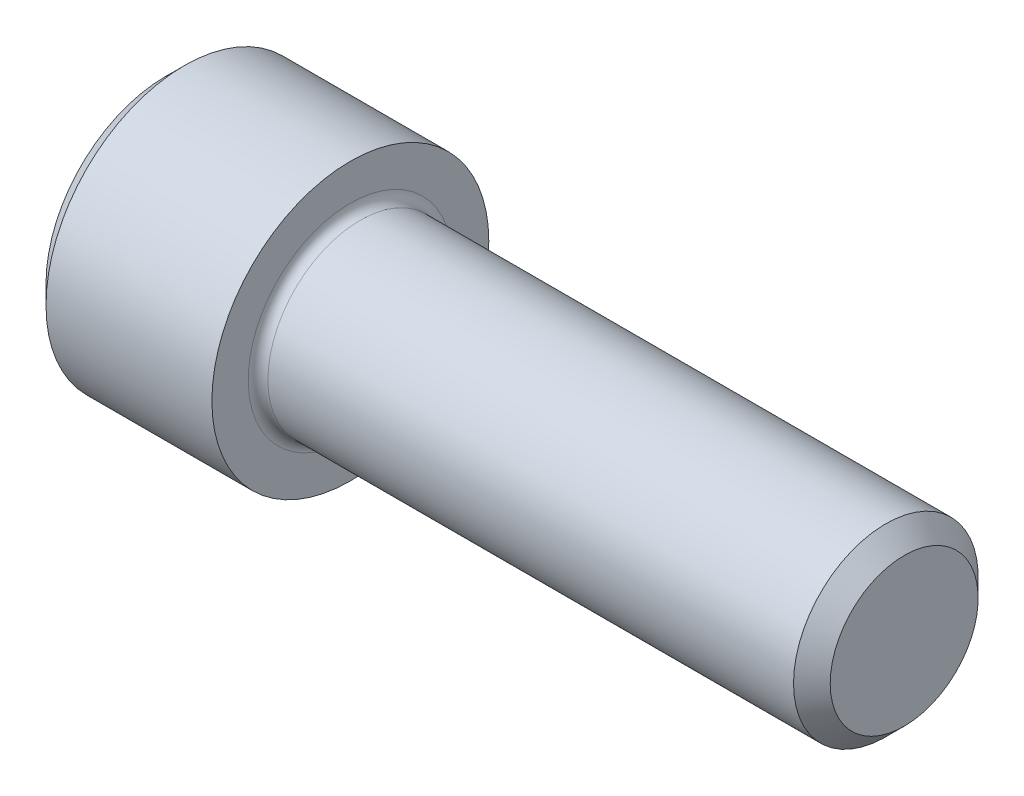
SolidWorks part; units mm, degrees
revolve "Base-Revolve" add sketch "BodySke"
sketch "BodySke" plane through (0, 0, 0) normal (0, 0, 1) x (1, 0, 0)
  line L0 (0, 0) -> (0, 6.1786)
  line L1 (0.9652, 7.1438) -> (9.525, 7.1438)
  line L2 (9.525, 7.1438) -> (9.525, 4.7625)
  line L3 (9.525, 4.7625) -> (37.1539, 4.7625)
  line L4 (38.1, 3.8163) -> (38.1, 0)
  line L5 (38.1, 0) -> (0, 0)
  line L6 (-31.75, 0) -> (127, 0) construction
  line L7 (0, 6.1786) -> (0.9652, 7.1438)
  line L8 (38.1, 3.8163) -> (37.1539, 4.7625)
  line L9 (0, -6.1786) -> (0.9652, -7.1437) construction
  line L10 (38.1, -3.8163) -> (37.1539, -4.7625) construction
  line L11 (11.1125, 9.525) -> (11.1125, 3.175) construction
  line L12 (9.525, 9.525) -> (9.525, 3.175) construction
  line L13 (0, 9.525) -> (0, 3.175) construction
  dimension "Diameter" = 9.525
  dimension "Head_ht" = 9.525
  dimension "Length" = 28.575
  dimension "Body_ch_ang" = 45
  dimension "Head_dia" = 14.2875
  dimension "Head_ch_ang" = 45
  dimension "Head_side_ht" = 8.5598
  dimension "Minor_dia" = 7.6327
  dimension "Advance" = 1.5875
  dimension "Thread_nom" = 28.575
  dimension "Thread_length" = 38.1
cosmetic thread "ThreadCosmetic" [suppressed]
fillet "Fillet1" radius 0.508 1 edges at (9.525, 0, 4.7625)
ref_plane "Plane1" through (0, 0, 0) normal (0, 0, 1) x (1, 0, 0)
ref_plane "Plane2" through (0, 0, 0) normal (0, 1, 0) x (1, 0, 0)
ref_plane "Plane3" through (0, 0, 0) normal (1, 0, 0) x (0, 0, -1)
sketch "Sketch2" plane through (0, 0, 0) normal (0, 0, 1) x (1, 0, 0)
  line L0 (0, 3.9688) -> (4.6228, 3.9688)
  line L1 (4.6228, 3.9688) -> (6.9142, 0)
  line L2 (-31.75, 0) -> (127, 0) construction
  line L3 (6.9142, 0) -> (0, 0)
  line L4 (0, 0) -> (0, 3.9688)
  line L5 (0, 6.1786) -> (0, -6.1786) construction
  line L6 (0, 0) -> (47.625, 0) construction
  line L7 (9.525, -7.1438) -> (9.525, 7.1438) construction
  dimension "D1" = 3.9688
  dimension "D2" = 60
revolve "Hex-PreBroach" cut sketch "Sketch2" angle 360 about L6
sketch "Sketch3" plane through (0, 0, 0) normal (-1, 0, 0) x (0, 0.5, 0.866)
  line L0 (2.2914, 3.9688) -> (-2.2914, 3.9688)
  line L1 (-2.2914, 3.9688) -> (-4.5827, 0)
  line L2 (2.2914, 3.9688) -> (4.5827, 0)
  line L3 (2.2914, -3.9688) -> (4.5827, 0)
  line L4 (2.2914, -3.9688) -> (-2.2914, -3.9688)
  line L5 (-2.2914, -3.9688) -> (-4.5827, 0)
  dimension "D1" = 3.9688
  dimension "D2" = 3.9688
  dimension "Hex_size" = 7.9375
extrude "Hex" cut sketch "Sketch3" against normal blind 4.6228
sketch "Sketch4" plane through (0, 0, 0) normal (-1, 0, 0) x (0, 0, 1)
  line L0 (0, 0) -> (4.826, 0)
  line L1 (0, 0) -> (6.1484, 3.5498) construction
  line L2 (0, 0) -> (2.413, 4.1794)
  line L3 (3.9437, 0.9277) -> (4.6393, 1.3293)
  line L4 (2.7753, 2.9514) -> (3.4709, 3.3531)
  arc A0 (3.9437, 0.9277) -> (2.7753, 2.9514) centre (0, 0) ccw
  arc A1 (4.826, 0) -> (4.6393, 1.3293) centre (0, 0) ccw
  arc A2 (2.413, 4.1794) -> (3.4709, 3.3531) centre (0, 0) cw
  dimension "D1" = 30
  dimension "D2" = 60
  dimension "Spline_p_dim" = 2.3368
  dimension "D3" = 1.1684
extrude "Spline" [suppressed] cut sketch "Sketch4" against normal blind 4.6228
pattern_circular "CirPattern1" [suppressed] count 6 every 60
sketch "Sketch5" plane through (0, 0, 0) normal (0, 0, 1) x (1, 0, 0)
  line L0 (-31.75, 0) -> (127, 0) construction
  line L2 (0, 6.1786) -> (0, -6.1786) construction
  circle A0 centre (3.1242, 0) radius 0.8065
  dimension "Drilled_hole_dia" = 1.6129
  dimension "Drilled_hole_loc" = 3.1242
extrude "Hole" [suppressed] cut sketch "Sketch5" against normal through all and the other way through all
pattern_circular "Drilled-4" [suppressed] count 2 every 60
pattern_circular "Drilled-6" [suppressed] count 3 every 60
sketch "ThdSchSke" plane through (0, 0, 0) normal (0, 0, 1) x (1, 0, 0)
  line L0 (11.1125, -3.8163) -> (10.45, -4.7625)
  line L1 (11.1125, -3.8163) -> (11.775, -4.7625)
  line L2 (11.775, -4.7625) -> (11.775, -5.9531)
  line L3 (-3.175, 0) -> (5.1513, 0) construction
  line L5 (11.775, -5.9531) -> (10.45, -5.9531)
  line L6 (10.45, -5.9531) -> (10.45, -4.7625)
  line L7 (0, 6.1786) -> (0, -6.1786) construction
  dimension "Thread_minor" = 7.6327
  dimension "Diameter" = 9.525
  dimension "Start" = 11.1125
revolve "ThreadSchematic" [suppressed] cut sketch "ThdSchSke" angle 360 about L3
pattern_linear "ThdSchPat" [suppressed]
equation "\"D2@Sketch3\" = \"Hex_size@Sketch3\" / 2"
equation "\"D1@Sketch3\" = \"Hex_size@Sketch3\" / 2"
equation "\"D1@Sketch2\" = \"Hex_size@Sketch3\" / 2"
equation "\"D3@Sketch4\" = \"Spline_p_dim@Sketch4\" / 2"
equation "\"Thread_minor@ThreadCosmetic\"  =  \"Minor_dia@BodySke\""
equation "\"D2@CirPattern1\" = 360 / \"Num_teeth@CirPattern1\""
equation "\"Wall_thickness@Sketch2\" = \"Head_ht@BodySke\" - \"Key_eng@Hex\""
equation "\"Thread_length@ThreadCosmetic\" = ((sgn( (\"Length@BodySke\" - \"Advance@BodySke\" ) - \"Thread_nom@BodySke\" )-1)*( (\"Length@BodySke\" - \"Advance@BodySke\" ) - \"Thread_nom@BodySke\" ))/-2+ \"Thread_nom@BodySke\""
equation "\"Thread_minor@ThdSchSke\" = \"Minor_dia@BodySke\""
equation "\"Diameter@ThdSchSke\" = \"Diameter@BodySke\""
equation "\"Overcut@ThdSchSke\" = \"Diameter@BodySke\" * 1.25"
equation "\"Start@ThdSchSke\" = \"Head_ht@BodySke\" + \"Length@BodySke\" - \"Thread_length@ThreadCosmetic\"  '---Non-countersunk---"
equation "\"Num_threads@ThdSchPat\" = int( \"Thread_length@ThreadCosmetic\" / \"Advance@BodySke\" + 0.999 )  + 1"
equation "\"Advance@ThdSchPat\" = \"Thread_length@ThreadCosmetic\" /  (\"Num_threads@ThdSchPat\" - 1) 'relax it"
equation "\"Num_threads@ThdSchPat\" = \"Num_threads@ThdSchPat\" - sgn( \"Num_threads@ThdSchPat\" - 1) '---chamfered tips only---"
